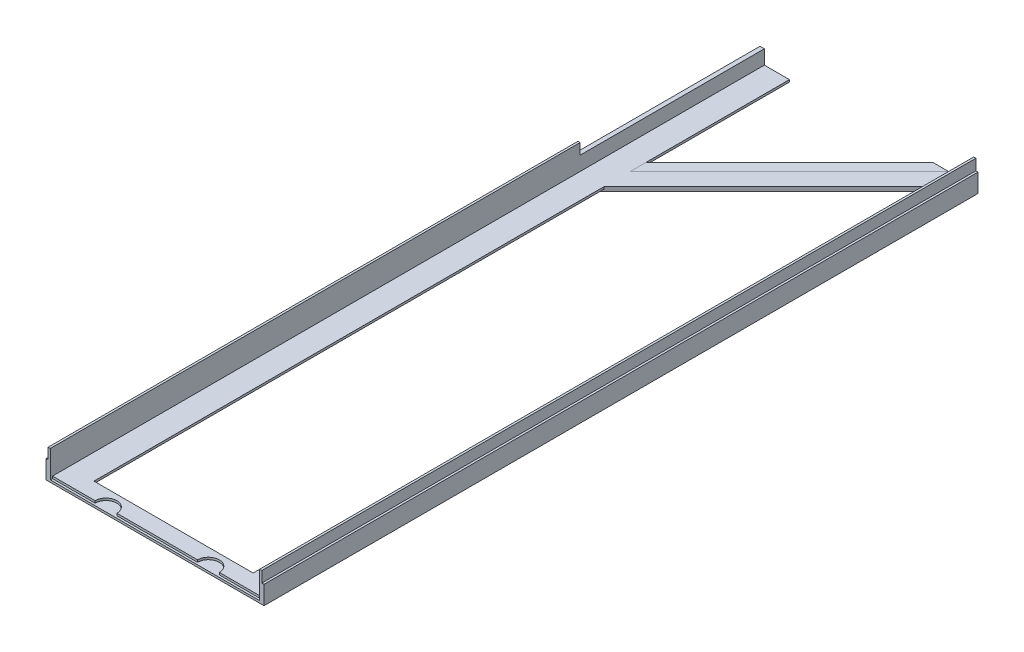
SolidWorks part; units mm, degrees
material "7075-O (SS)"
ref_plane "Front Plane" through (0, 0, 0) normal (0, 0, 1) x (1, 0, 0)
ref_plane "Top Plane" through (0, 0, 0) normal (0, 1, 0) x (1, 0, 0)
ref_plane "Right Plane" through (0, 0, 0) normal (1, 0, 0) x (0, 0, -1)
sketch "Sketch1" plane through (0, 0, 0) normal (0, 0, 1) x (1, 0, 0)
  line L0 (0, 0) -> (0, 8.5)
  line L1 (0, 8.5) -> (1, 8.5)
  line L2 (1, 8.5) -> (1, 13.5)
  line L3 (1, 13.5) -> (2, 13.5)
  line L4 (2, 13.5) -> (2, 2)
  line L5 (2, 2) -> (13.5, 2)
  line L6 (13.5, 2) -> (13.5, 1)
  line L7 (13.5, 1) -> (8.5, 1)
  line L8 (8.5, 1) -> (8.5, 0)
  line L9 (8.5, 0) -> (0, 0)
  line L10 (100, 0) -> (91.5, 0)
  line L11 (91.5, 0) -> (91.5, 1)
  line L12 (91.5, 1) -> (86.5, 1)
  line L13 (86.5, 1) -> (86.5, 2)
  line L14 (86.5, 2) -> (98, 2)
  line L15 (98, 2) -> (98, 13.5)
  line L16 (98, 13.5) -> (99, 13.5)
  line L17 (99, 13.5) -> (99, 8.5)
  line L18 (99, 8.5) -> (100, 8.5)
  line L19 (100, 8.5) -> (100, 0)
  dimension "D1" = 8.5
  dimension "D2" = 8.5
  dimension "D3" = 1
  dimension "D4" = 1
  dimension "D5" = 1
  dimension "D6" = 1
  dimension "D7" = 5
  dimension "D8" = 5
  dimension "D9" = 8.5
  dimension "D10" = 5
  dimension "D11" = 1
  dimension "D12" = 1
  dimension "D13" = 1
  dimension "D14" = 1
  dimension "D15" = 8.5
  dimension "D16" = 5
  dimension "D17" = 100
extrude "Boss-Extrude1" add sketch "Sketch1" along normal blind 327.5
sketch "Sketch2" plane through (0, 2, 0) normal (0, 1, 0) x (1, 0, 0)
  line L0 (86.5, 0) -> (13.5, -73)
  line L1 (13.5, -327.5) -> (13.5, 0) construction
  line L2 (13.5, -73) -> (13.5, -85.0208)
  line L3 (13.5, -85.0208) -> (86.5, -12.0208)
  line L4 (86.5, -327.5) -> (86.5, 0) construction
  line L5 (86.5, -12.0208) -> (86.5, 0)
  dimension "D1" = 8.5
  dimension "D2" = 45
extrude "Boss-Extrude2" add sketch "Sketch2" against normal blind 2
sketch "Sketch3" plane through (0, 1, 0) normal (0, -1, 0) x (1, 0, 0)
  line L0 (13.5, 85.0208) -> (8.5, 90.0208)
  line L1 (8.5, 327.5) -> (8.5, 0) construction
  line L2 (13.5, 73) -> (8.5, 78)
  line L3 (8.5, 78) -> (8.5, 90.0208)
  line L4 (13.5, 85.0208) -> (13.5, 73)
  line L5 (13.5, 85.0208) -> (86.5, 12.0208) construction
  line L6 (86.5, 0) -> (13.5, 73) construction
  line L7 (86.5, 12.0208) -> (91.5, 7.0208)
  line L8 (91.5, 327.5) -> (91.5, 0) construction
  line L9 (91.5, 7.0208) -> (91.5, 0)
  line L10 (91.5, 0) -> (86.5, 0)
  line L11 (86.5, 0) -> (86.5, 12.0208)
  line M5 (13.5, 73) -> (13.5, 85.0208)
  line M8 (8.5, 327.5) -> (8.5, 0)
  dimension "D1" = 180
  dimension "D2" = 180
  dimension "D3" = 180
extrude "Boss-Extrude4" add sketch "Sketch3" along normal blind 1 contours L2 L0 M5 M8 | L11 L10 L9 L7
sketch "Sketch4" plane through (0, 0, 0) normal (0, -1, 0) x (1, 0, 0)
  line L0 (0, 327.5) -> (0, 0) construction
  line L1 (100, 327.5) -> (0, 327.5)
  line L2 (100, 327.5) -> (100, 319)
  line L3 (100, 319) -> (0, 319)
  line L4 (0, 327.5) -> (0, 319)
  dimension "D1" = 8.5
extrude "Boss-Extrude5" add sketch "Sketch4" against normal blind 2
sketch "Sketch5" plane through (0, 2, 0) normal (0, 1, 0) x (1, 0, 0)
  line L0 (13.5, -65.9289) -> (79.4289, 0)
  line L1 (13.5, -73) -> (13.5, 0) construction
  line L2 (79.4289, 0) -> (86.5, 0)
  line L3 (86.5, 0) -> (13.5, -73)
  line L4 (13.5, -73) -> (13.5, -65.9289)
  dimension "D1" = 5
extrude "Boss-Extrude6" add sketch "Sketch5" against normal blind 1 separate body
sketch "Sketch6" plane through (0, 2, 0) normal (0, 1, 0) x (1, 0, 0)
  line L0 (98, -327.5) -> (98, 0) construction
  line L1 (2, -327.5) -> (98, -327.5)
  line L2 (2, -327.5) -> (2, -326.5)
  line L3 (2, -326.5) -> (98, -326.5)
  line L4 (98, -327.5) -> (98, -326.5)
  line L5 (1, -327.5) -> (1, 0) construction
  line L6 (99, -327.5) -> (99, 0) construction
  circle A0 centre (26.5, -326.5) radius 5
  circle A1 centre (73.5, -326.5) radius 5
  dimension "D2" = 10
  dimension "D3" = 10
  dimension "D1" = 1
  dimension "D4" = 25.5
  dimension "D5" = 25.5
extrude "Cut-Extrude1" cut sketch "Sketch6" against normal blind 1 contours L3 A1 | A0
sketch "Sketch7" plane through (0, 0, 0) normal (0, 0, -1) x (-1, 0, 0)
  line L0 (-2, 2) -> (-2, 13.5) construction
  line L1 (-1, 13.5) -> (-2, 13.5)
  line L2 (-1, 13.5) -> (-1, 8.5)
  line L3 (-1, 8.5) -> (-2, 8.5)
  line L4 (-2, 13.5) -> (-2, 8.5)
  point P7 (-1.5, 13.5)
  dimension "D1" = 5
extrude "Cut-Extrude2" cut sketch "Sketch7" against normal blind 84.5
